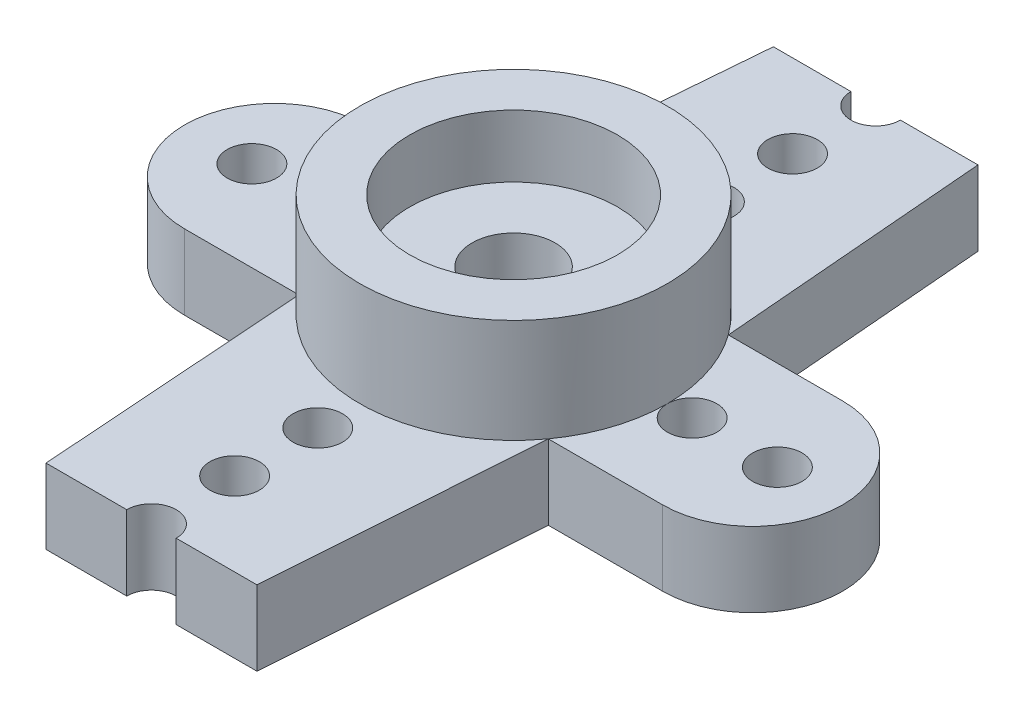
SolidWorks part; units mm, degrees
ref_plane "Front Plane" through (0, 0, 0) normal (0, 0, 1) x (1, 0, 0)
ref_plane "Top Plane" through (0, 0, 0) normal (0, 1, 0) x (1, 0, 0)
ref_plane "Right Plane" through (0, 0, 0) normal (1, 0, 0) x (0, 0, -1)
sketch "Sketch2" plane through (0, 0, 0) normal (0, 1, 0) x (1, 0, 0)
  line L0 (0, 0) -> (-0.5987, 0) construction
  line L1 (-17.8198, 0) -> (32.1802, 0) construction
  line L2 (-2.4609, 8.71) -> (-0.595, 8.71)
  line L3 (-5.7505, 2.165) -> (-3.0005, 2.165)
  line L4 (-3.0005, 2.165) -> (-2.4609, 8.71)
  line L5 (-5.7505, -2.165) -> (-3.0005, -2.165)
  line L6 (-3.0005, -2.165) -> (-2.5372, -8.71)
  line L7 (0.595, 8.71) -> (2.4609, 8.71)
  line L8 (0.595, -8.71) -> (2.5372, -8.71)
  line L9 (5.7505, -2.165) -> (3.0005, -2.165)
  line L10 (3.0005, 2.165) -> (2.4609, 8.71)
  line L11 (5.7505, 2.165) -> (3.0005, 2.165)
  line L12 (3.0005, -2.165) -> (2.5372, -8.71)
  line L14 (0, 8.115) -> (0, -8.115) construction
  line L19 (-0.595, -8.71) -> (-2.5372, -8.71)
  circle A0 centre (0, 0) radius 2.5
  circle A1 centre (-4.295, 0) radius 0.595
  circle A2 centre (-6.295, 0) radius 0.595
  arc A4 (-5.7505, 2.165) -> (-7.9155, 0) centre (-5.7505, 0) ccw
  circle A5 centre (0, 4.71) radius 0.595
  circle A6 centre (0, 6.71) radius 0.595
  arc A7 (-0.595, 8.71) -> (0.595, 8.71) centre (0, 8.71) ccw
  arc A11 (7.9155, 0) -> (5.7505, -2.165) centre (5.7505, 0) cw
  arc A12 (-7.9155, 0) -> (-5.7505, -2.165) centre (-5.7505, 0) ccw
  circle A13 centre (0, -4.71) radius 0.595
  circle A14 centre (0, -6.71) radius 0.595
  arc A15 (-0.595, -8.71) -> (0.595, -8.71) centre (0, -8.71) cw
  arc A21 (5.7505, 2.165) -> (7.9155, 0) centre (5.7505, 0) cw
  circle A22 centre (6.345, 0) radius 0.595
  circle A23 centre (4.295, 0) radius 0.595
  arc A28 (0, -17.305) -> (0, -16.115) centre (0, -16.71) cw [skipped]
  arc A29 (0, -15.305) -> (0, -14.115) centre (0, -14.71) cw [skipped]
  arc A30 (0, -13.305) -> (0, -12.115) centre (0, -12.71) cw [skipped]
  arc A31 (0, -11.305) -> (0, -10.115) centre (0, -10.71) cw [skipped]
  dimension "D1" = 5
  dimension "D3" = 1.19
  dimension "D4" = 1.19
  dimension "D13" = 2.165
  dimension "D20" = 2.165
  dimension "D2" = 2
  dimension "D6" = 4.71
  dimension "D7" = 2.75
  dimension "D10" = 7
  dimension "D5" = 12.64
extrude "Boss-Extrude1" add sketch "Sketch2" along normal blind 1.8
sketch "Sketch3" plane through (0, 1.8, 0) normal (0, 1, 0) x (1, 0, 0)
  circle A0 centre (0, 0) radius 3.7
  circle A1 centre (0, 0) radius 2.5
  dimension "D1" = 5
extrude "Boss-Extrude2" add sketch "Sketch3" along normal blind 2.5
ref_plane "Plane1" through (0, 1, 0) normal (0, -1, 0) x (-1, 0, 0)
sketch "Sketch4" plane through (0, 1, 0) normal (0, -1, 0) x (-1, 0, 0)
  circle A0 centre (0, 0) radius 2.5
  circle A1 centre (0, 0) radius 1
  dimension "D1" = 2
extrude "Boss-Extrude3" add sketch "Sketch4" against normal blind 1.8
